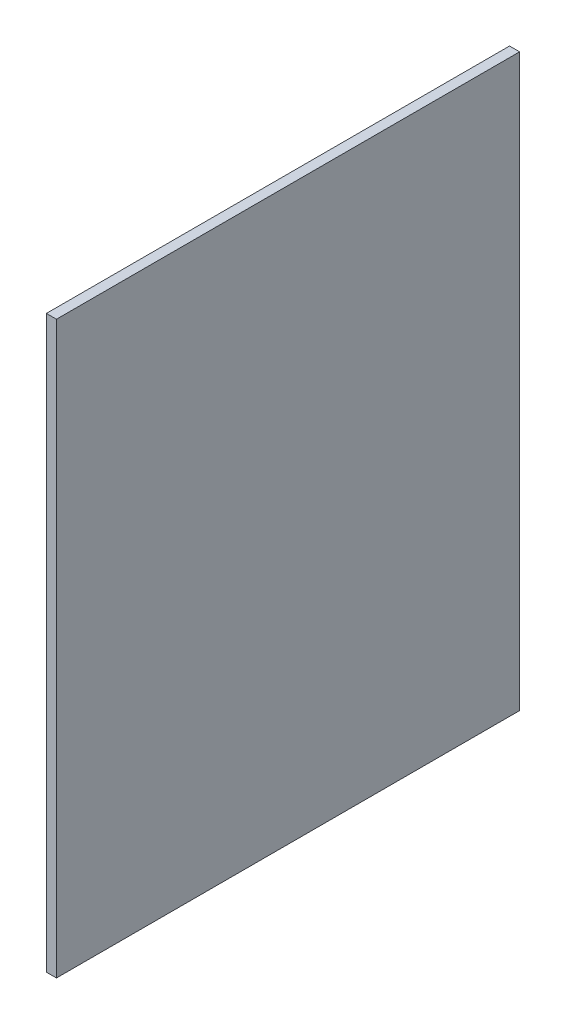
SolidWorks part; units mm, degrees
material "Glass"
ref_plane "Front Plane" through (0, 0, 0) normal (0, 0, 1) x (1, 0, 0)
ref_plane "Top Plane" through (0, 0, 0) normal (0, 1, 0) x (1, 0, 0)
ref_plane "Right Plane" through (0, 0, 0) normal (1, 0, 0) x (0, 0, -1)
sketch "Sketch1" plane through (0, 0, 0) normal (1, 0, 0) x (0, 0, -1)
  line L1 (-36.487, 1030.425) -> (839.813, 1030.425)
  line L2 (-36.487, 1030.425) -> (-36.487, -49.075)
  line L3 (-36.487, -49.075) -> (839.813, -49.075)
  line L4 (839.813, 1030.425) -> (839.813, -49.075)
extrude "Boss-Extrude1" add sketch "Sketch1" along normal blind 19.05 contours L2 L1 L4 L3
